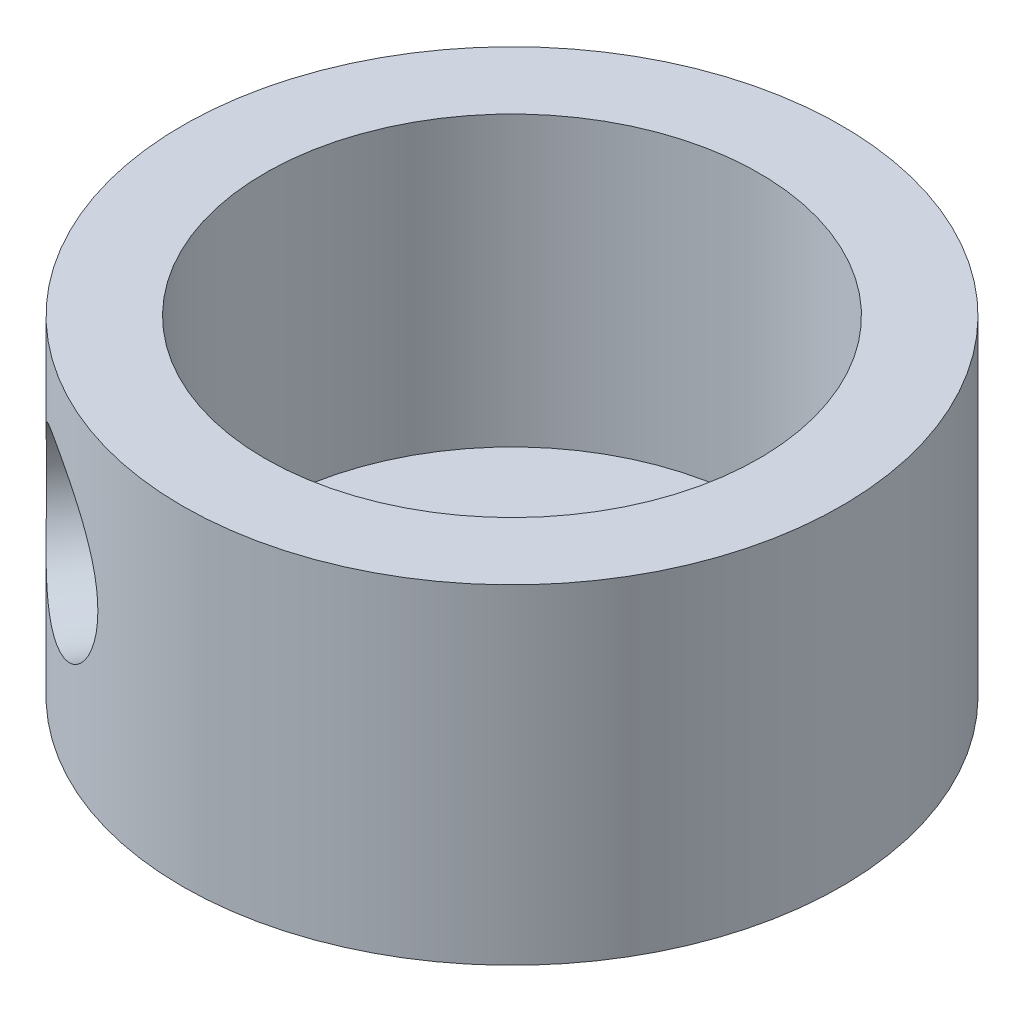
SolidWorks part; units mm, degrees
ref_plane "前基準面" through (0, 0, 0) normal (0, 0, 1) x (1, 0, 0)
ref_plane "上基準面" through (0, 0, 0) normal (0, 1, 0) x (1, 0, 0)
ref_plane "右基準面" through (0, 0, 0) normal (1, 0, 0) x (0, 0, -1)
sketch "草圖1" plane through (0, 0, 0) normal (0, 1, 0) x (1, 0, 0)
  circle A0 centre (0, 0) radius 40
  dimension "D1" = 80
extrude "填料-伸長1" add sketch "草圖1" along normal blind 40
sketch "草圖3" plane through (0, 40, 0) normal (0, 1, 0) x (1, 0, 0)
  circle A0 centre (0, 0) radius 30
  circle A1 centre (0, 0) radius 40 construction
  dimension "D1" = 10
extrude "除料-伸長2" cut sketch "草圖3" against normal blind 35
hole_wizard "Ø21.0 (21) 直徑孔1" positions "3D草圖1" profile "草圖4" hole size "Ø21.0" standard "JIS"
sketch3d "3D草圖1"
  point P0 (-21.7448, 21.9418, 33.5733)
sketch "草圖4" plane through (-21.7448, 21.9418, 33.5733) normal (0, 1, 0) x (0.8393, 0, 0.5436)
  line L0 (0, 0) -> (0, 10)
  line L1 (0, 10) -> (10.5, 10)
  line L2 (10.5, 10) -> (10.5, 0)
  line L5 (10.5, 0) -> (0, 0)
  line L11 (0, -6.35) -> (0, 107.95) construction
  dimension "貫穿孔直徑" = 21
  dimension "貫穿孔深度" = 10
